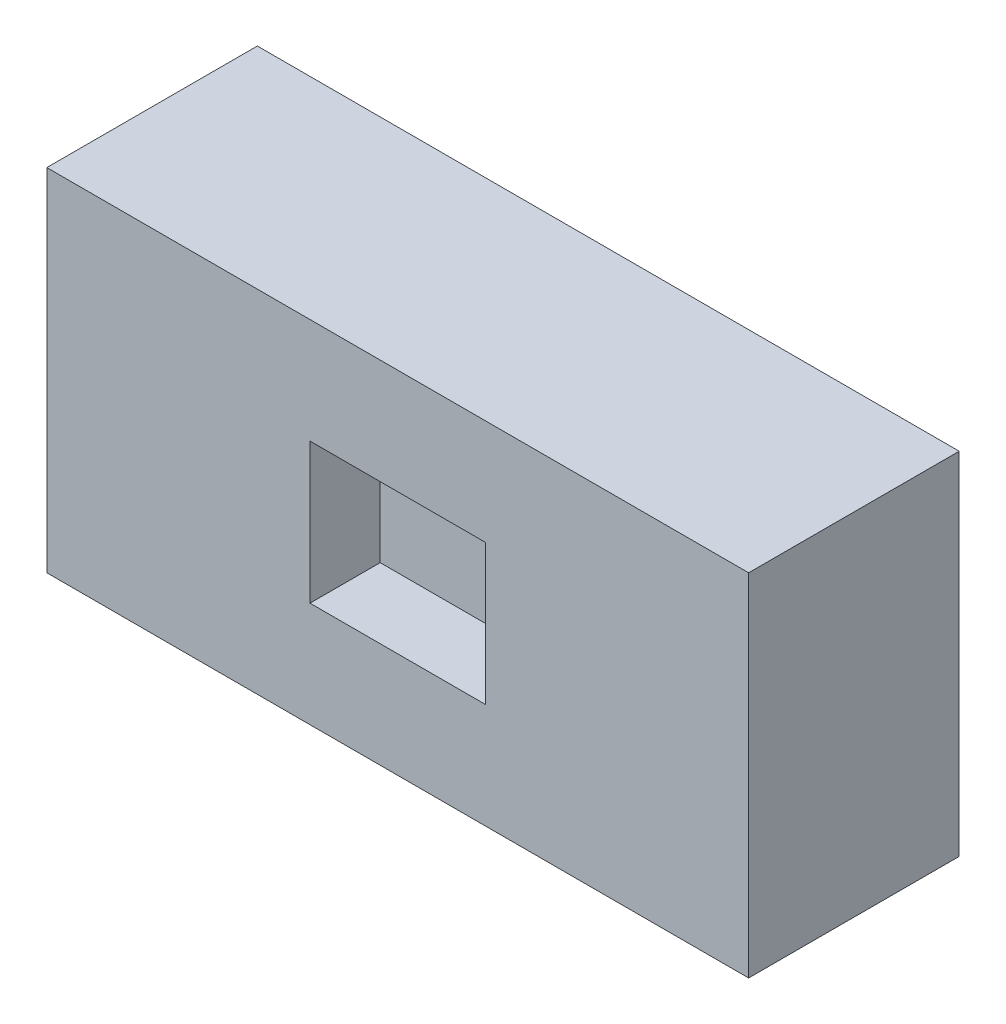
SolidWorks part; units mm, degrees
ref_plane "Front Plane" through (0, 0, 0) normal (0, 0, 1) x (1, 0, 0)
ref_plane "Top Plane" through (0, 0, 0) normal (0, 1, 0) x (1, 0, 0)
ref_plane "Right Plane" through (0, 0, 0) normal (1, 0, 0) x (0, 0, -1)
sketch "RectangleSketch" plane through (0, 0, 0) normal (0, 0, 1) x (1, 0, 0)
  line L1 (0, 0) -> (40, 0)
  line L2 (0, 0) -> (0, 20)
  line L3 (0, 20) -> (40, 20)
  line L4 (40, 0) -> (40, 20)
  dimension "width_mm" = 40
  dimension "height_mm" = 20
extrude "BlindBoss" add sketch "RectangleSketch" along normal blind 12 separate body
sketch "CutSketch" plane through (0, 0, 12) normal (0, 0, 1) x (1, 0, 0)
  line L1 (15, 6) -> (25, 6)
  line L2 (15, 6) -> (15, 14)
  line L3 (15, 14) -> (25, 14)
  line L4 (25, 6) -> (25, 14)
  dimension "cut_width_mm" = 10
  dimension "cut_height_mm" = 8
  dimension "cut_left_mm" = 15
  dimension "cut_bottom_mm" = 6
extrude "BlindCut" cut sketch "CutSketch" against normal blind 4
equation "\"cut_left_mm@CutSketch\" = (\"width_mm@RectangleSketch\" - \"cut_width_mm@CutSketch\") / 2"
equation "\"cut_bottom_mm@CutSketch\" = (\"height_mm@RectangleSketch\" - \"cut_height_mm@CutSketch\") / 2"
